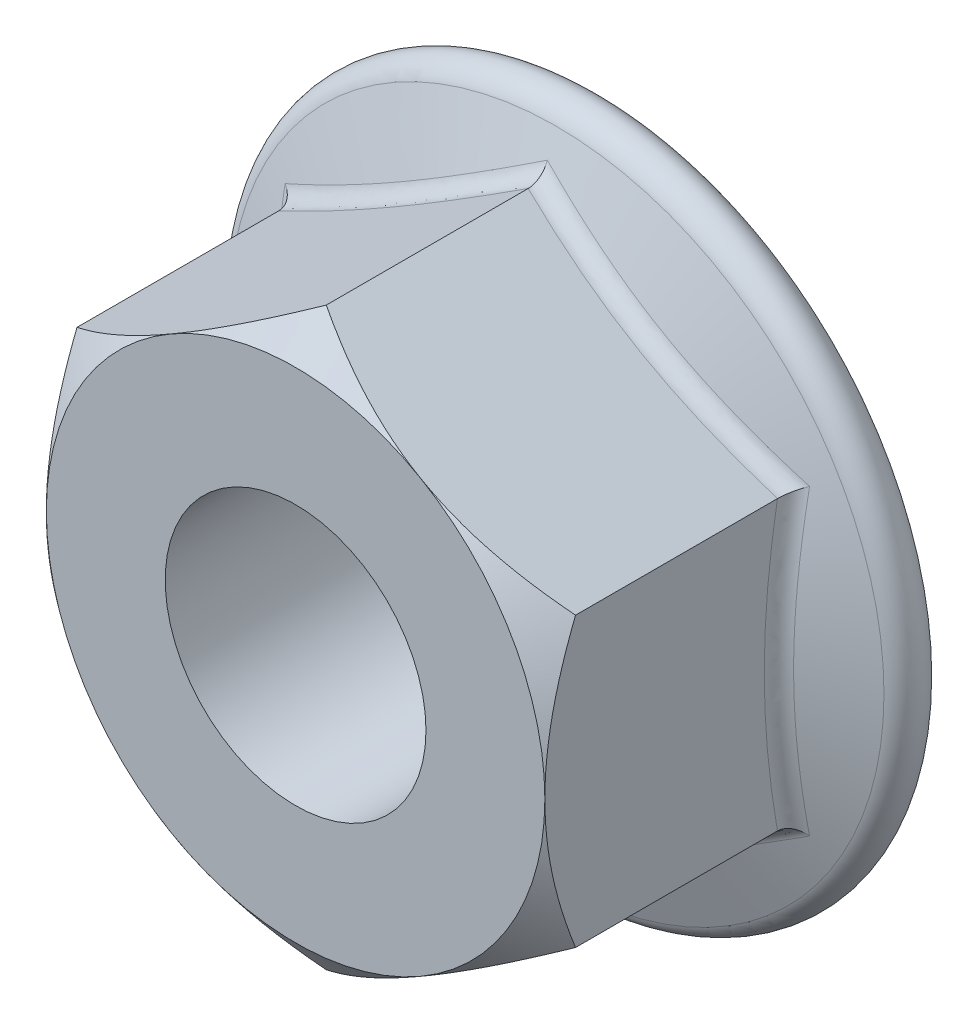
SolidWorks part; units mm, degrees
extrude "BaseNut" add sketch "BaseNutSke" against normal blind 8
sketch "BaseNutSke" plane through (0, 0, 0) normal (0, 0, 1) x (1, 0, 0)
  line L6 (6.5, 3.7528) -> (6.5, -3.7528)
  line L7 (-6.5, 3.7528) -> (-6.5, -3.7528)
  line L8 (6.5, 3.7528) -> (0, 7.5056)
  line L9 (0, 7.5056) -> (-6.5, 3.7528)
  line L10 (-6.5, -3.7528) -> (0, -7.5056)
  line L11 (0, -7.5056) -> (6.5, -3.7528)
  circle A0 centre (0, 0) radius 3.4
  dimension "Tap_drill" = 6.8
  dimension "Width_flats" = 13
  dimension "D2" = 6.5
  dimension "D3" = 6.5
  dimension "D1" = 120
  dimension "D4" = 6.5
cosmetic thread "ThreadCosmetic" parameters "Thread_major"=8
pattern_linear "ThdSchPat" [suppressed]
revolve "ThreadSchematic" [suppressed] cut sketch "ThdSchSke" angle 360 about L6
sketch "ThdSchSke" plane through (0, 0, 0) normal (0, 1, 0) x (1, 0, 0)
  line L0 (-4, 0.0254) -> (-3.4, 0.4455)
  line L1 (-3.4, 0.4455) -> (-1.7, 0.4455)
  line L2 (-1.7, 0.4455) -> (-1.7, -0.3947)
  line L3 (-1.7, -0.3947) -> (-3.4, -0.3947)
  line L4 (-3.4, -0.3947) -> (-4, 0.0254)
  line L5 (-3.175, 1.25) -> (3.175, 1.25) construction
  line L6 (0, 1.25) -> (0, -2.9874) construction
  line L7 (0, 8) -> (0, 0) construction
  dimension "Thread_major" = 8
  dimension "SideAngle" = 55
  dimension "D1" = 0.0254
material "AISI 316 Нержавеющая сталь, лист (SS)"
ref_plane "Plane1" through (0, 0, 0) normal (0, 0, 1) x (1, 0, 0)
ref_plane "Plane2" through (0, 0, 0) normal (0, 1, 0) x (1, 0, 0)
ref_plane "Plane3" through (0, 0, 0) normal (1, 0, 0) x (0, 0, -1)
other "Configuration Table"
sketch "Sketch6" plane through (0, 0, 0) normal (1, 0, 0) x (0, 0, -1)
  line L0 (4.9281, 3.4) -> (6.8, 8.5429)
  line L1 (8, 3.4) -> (8, 8.3313)
  line L2 (6.8, 32.2909) -> (6.8, 8.5429) construction
  line L3 (23.7075, 8.95) -> (19.5103, 8.95) construction
  line L4 (8, 3.4) -> (4.9281, 3.4)
  line L5 (23.7075, -8.95) -> (19.5103, -8.95) construction
  line L6 (8, 3.7528) -> (8, 7.5056) construction
  line L7 (0, 0) -> (32.9582, 0) construction
  line L8 (8, -3.4) -> (4.9281, -3.4) construction
  line L9 (8, 0) -> (0, 0) construction
  arc A0 (8, 8.3313) -> (6.8, 8.5429) centre (7.3813, 8.3313) ccw
  dimension "Flange_thickness" = 1.2
  dimension "Flange_dia" = 17.9
  dimension "D2" = 20
revolve "Flange" add sketch "Sketch6" angle 360 about L7
sketch "Sketch3" plane through (0, 0, 0) normal (1, 0, 0) x (0, 0, -1)
  line L0 (8, 6.5) -> (7.2, 7.5056) construction
  line L1 (7.2, 7.5056) -> (7.2, 20.2056) construction
  line L2 (7.2, 20.2056) -> (20.7, 20.2056) construction
  line L3 (20.7, 20.2056) -> (20.7, 6.5) construction
  line L4 (20.7, 6.5) -> (8, 6.5) construction
  line L5 (8, 3.7528) -> (8, 7.5056) construction
  line L6 (6.4224, 7.5056) -> (0, 7.5056) construction
  line L7 (0, 0) -> (38.6776, 0) construction
  line L8 (8, 0) -> (0, 0) construction
  line L9 (4, 7.5056) -> (4, 44.222) construction
  line L10 (0.8, 20.2056) -> (-12.7, 20.2056)
  line L11 (-12.7, 20.2056) -> (-12.7, 6.5)
  line L12 (-12.7, 6.5) -> (0, 6.5)
  line L13 (0, 6.5) -> (0.8, 7.5056)
  line L14 (0.8, 7.5056) -> (0.8, 20.2056)
  line L16 (6.4224, 7.5056) -> (0, 7.5056) construction
  dimension "D2" = 0.8
  dimension "D4" = 12.7
  dimension "D3" = 12.7
  dimension "D5" = 4
revolve "Double-Chamfer" cut sketch "Sketch3" angle 360 about L7
fillet "FlangeFillet" radius 0.48 6 edges
sketch "Sketch5" plane through (0, 0, 0) normal (1, 0, 0) x (0, 0, -1)
  line L0 (33.3492, 4) -> (32.8871, 3.34)
  line L1 (33.4, 4) -> (33.3492, 4)
  line L2 (33.4, 4) -> (33.4, 3.34)
  line L3 (33.4, 3.34) -> (32.8871, 3.34)
  line L6 (-50.8, 4) -> (-50.7492, 4)
  line L7 (-50.7492, 4) -> (-50.2871, 3.34)
  line L9 (-50.2871, 3.34) -> (-50.8, 3.34)
  line L10 (-50.8, 3.34) -> (-50.8, 4)
  line L11 (25.0375, 0) -> (38.388, 0) construction
  line L12 (8, 0) -> (0, 0) construction
  dimension "D1" = 35
  dimension "ThreadMajor" = 4
  dimension "Offset1" = 33.4
revolve "EndChamfer" [suppressed] cut sketch "Sketch5" angle 360 about L11
equation "\"D2@BaseNutSke\" = \"Width_flats@BaseNutSke\" / 2"
equation "\"D3@BaseNutSke\" = \"Width_flats@BaseNutSke\" / 2"
equation "\"D1@Sketch3\" = \"Width_flats@BaseNutSke\" /2"
equation "\"D2@Sketch3\" = \"Thread_major@ThreadCosmetic\" *.1"
equation "\"D4@BaseNutSke\" = \"D3@BaseNutSke\""
equation "\"Thread_major@ThdSchSke\" = \"Thread_major@ThreadCosmetic\""
equation "\"Tap_Drill@ThdSchSke\" = \"Tap_drill@BaseNutSke\""
equation "\"OverCut@ThdSchSke\" = \"Tap_Drill@ThdSchSke\" * 0.5"
equation "\"Num_threads@ThdSchPat\" = int(  ( \"Thickness@BaseNut\" - 0.0508 ) / \"Advance@ThdSchSke\" + 0.999 )  + 1"
equation "\"Advance@ThdSchPat\" = ( \"Thickness@BaseNut\" - 0.0508 ) /  (\"Num_threads@ThdSchPat\" - 1) 'relax it"
equation "' \"Num_threads@ThdSchPat\" = \"Num_threads@ThdSchPat\" - sgn( \"Num_threads@ThdSchPat\" - 1) '---chamfered tips only---"
equation "\"ThreadMajor@Sketch5\" = \"Thread_major@ThreadCosmetic\" * 0.5"
equation "\"ChamferDepth@Sketch5\" = (\"Thread_major@ThreadCosmetic\" - \"Tap_drill@BaseNutSke\") * 0.55"
equation "\"Offset1@Sketch5\" = \"Thickness@BaseNut\" + 0.0254"
equation "\"Offset2@Sketch5\" = \"Offset1@Sketch5\" + 0.0508"
equation "\"D1@Sketch6\" = \"Tap_drill@BaseNutSke\""
equation "\"D5@Sketch3\" = \"Thickness@BaseNut\" / 2"
